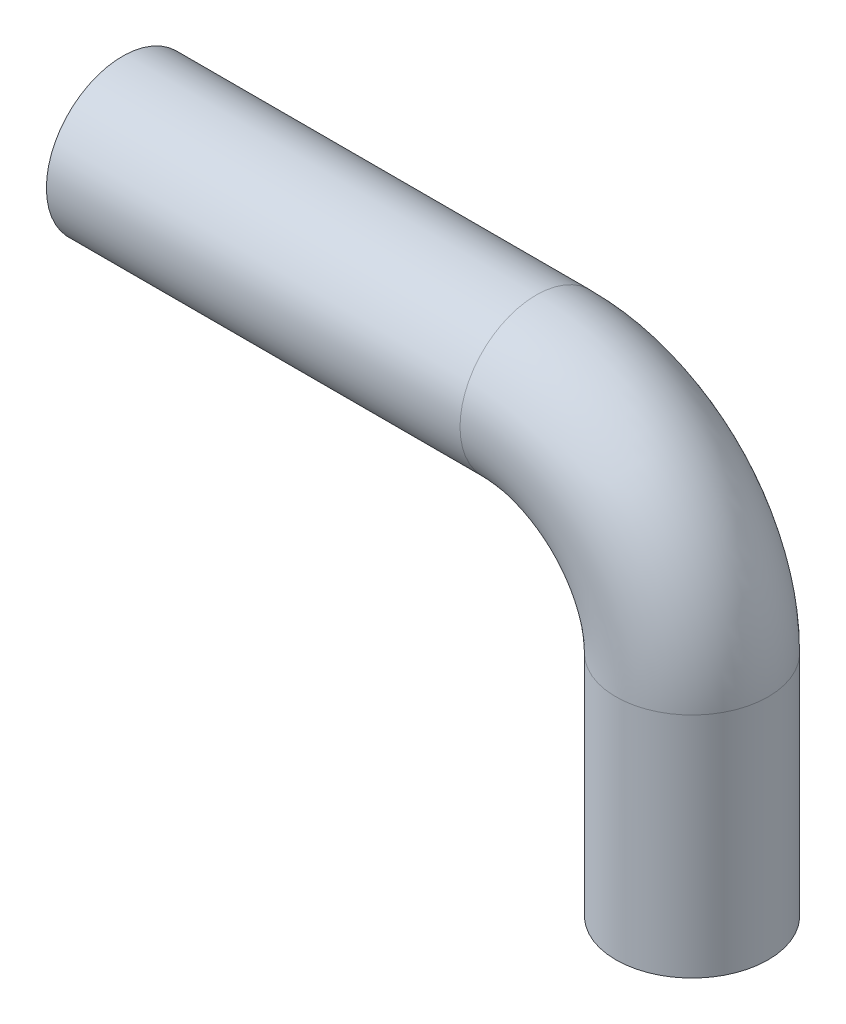
SolidWorks part; units mm, degrees
ref_plane "Alzado" through (0, 0, 0) normal (0, 0, 1) x (1, 0, 0)
ref_plane "Planta" through (0, 0, 0) normal (0, 1, 0) x (1, 0, 0)
ref_plane "Vista lateral" through (0, 0, 0) normal (1, 0, 0) x (0, 0, -1)
sketch "Croquis1" plane through (0, 0, 0) normal (0, 1, 0) x (1, 0, 0)
  circle A0 centre (0, 0) radius 12.7
  dimension "D1" = 25.4
extrude "Saliente-Extruir1" add sketch "Croquis1" along normal blind 10
sketch3d "Croquis3D1"
  line L0 (0, 10, 0) -> (0, 38, 0)
  line L1 (0, 10, 0) -> (0, 0, 0) construction
  line L2 (-26, 64, 0) -> (-95, 64, 0)
  arc A0 (0, 38, 0) -> (-26, 64, 0) centre (-26, 38, 0) ccw
  point P7 (0, 64, 0)
  point P8 (-26, 38, 26)
  dimension "D3" = 26
  dimension "D1" = 54
  dimension "D2" = 95
sketch "Croquis2" plane through (0, 10, 0) normal (0, 1, 0) x (1, 0, 0)
  circle A0 centre (0, 0) radius 12.7
sweep "Barrer1" add profiles "Croquis2" path "Croquis3D1"
